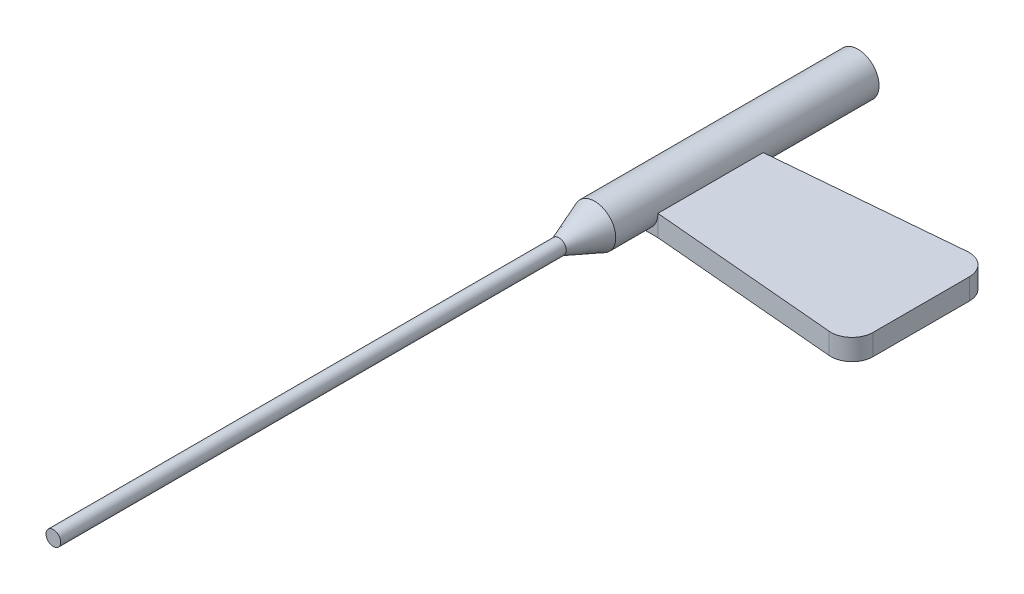
SolidWorks part; units mm, degrees
ref_plane "前视基准面" through (0, 0, 0) normal (0, 0, 1) x (1, 0, 0)
ref_plane "上视基准面" through (0, 0, 0) normal (0, 1, 0) x (1, 0, 0)
ref_plane "右视基准面" through (0, 0, 0) normal (1, 0, 0) x (0, 0, -1)
sketch "草图1" plane through (0, 0, 0) normal (0, 0, 1) x (1, 0, 0)
  circle A0 centre (0, 0) radius 1
  dimension "D1" = 2
extrude "凸台-拉伸1" add sketch "草图1" along normal blind 12.5
sketch "草图2" plane through (0, 0, 0) normal (0, 1, 0) x (1, 0, 0)
  line L0 (1, -12.5) -> (1, -10.5) construction
  line L1 (1, -12.5) -> (1, 0) construction
  line L2 (1, -10.5) -> (1, -5.5)
  line L3 (1, -10.5) -> (11, -11.3749)
  line L4 (11, -11.3749) -> (11, -4.6251)
  line L5 (11, -4.6251) -> (1, -5.5)
  dimension "D1" = 2
  dimension "D2" = 5
  dimension "D3" = 95
  dimension "D4" = 10
  dimension "D5" = 95
extrude "凸台-拉伸2" add sketch "草图2" against normal blind 1 separate body
sketch "草图3" plane through (1, 0, 0) normal (-1, 0, 0) x (0, 0, 1)
  line L4 (10.5, 0) -> (5.5, 0)
  line L5 (10.5, -1) -> (10.5, 0)
  line L6 (5.5, -1) -> (10.5, -1)
  line L7 (5.5, 0) -> (5.5, -1)
  line L8 (10.5, 0) -> (5.5, 0)
  line L9 (10.5, -1) -> (10.5, 0)
  line L10 (5.5, -1) -> (10.5, -1)
  line L11 (5.5, 0) -> (5.5, -1)
  dimension "D1" = 0
extrude "凸台-拉伸3" add sketch "草图3" along normal up to next
sketch "草图5" plane through (0, 0, 0) normal (0, 1, 0) x (1, 0, 0)
  line L0 (-1, -12.5) -> (-0.35, -14.2)
  line L1 (0, -14.2) -> (0, -12.5)
  line L2 (-1, -12.5) -> (1, -12.5) construction
  line L4 (-0.35, -14.2) -> (-0.35, -38.2)
  line L5 (-0.35, -38.2) -> (0, -38.2)
  line L6 (0, -38.2) -> (0, -14.2)
  line L7 (-1, -12.5) -> (0, -12.5)
  dimension "D1" = 0.35
  dimension "D2" = 1.7
  dimension "D3" = 24
revolve "旋转2" add sketch "草图5" angle 360 about L6
fillet "圆角1" radius 1 2 edges at (11, -0.5, 4.6251) (11, -0.5, 11.3749)
